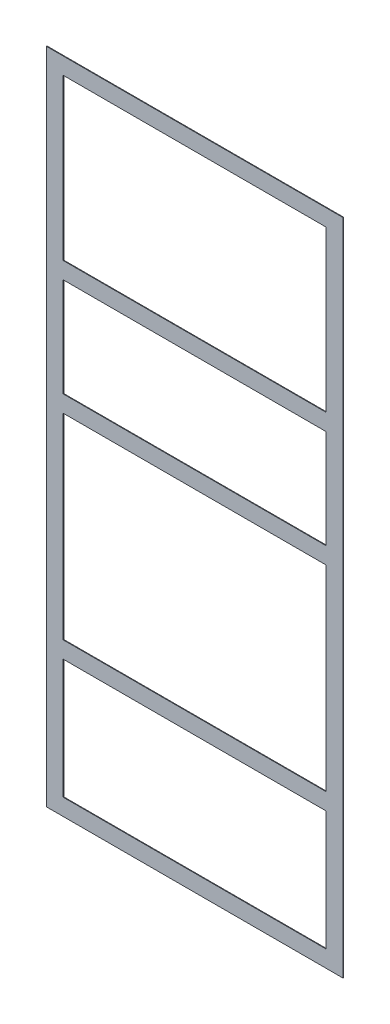
SolidWorks part; units mm, degrees
ref_plane "Alzado" through (0, 0, 0) normal (0, 0, 1) x (1, 0, 0)
ref_plane "Planta" through (0, 0, 0) normal (0, 1, 0) x (1, 0, 0)
ref_plane "Vista lateral" through (0, 0, 0) normal (1, 0, 0) x (0, 0, -1)
sketch "Croquis1" plane through (0, 0, 0) normal (0, 0, 1) x (1, 0, 0)
  line L1 (-450, 1000) -> (450, 1000)
  line L2 (-450, 1000) -> (-450, -1000)
  line L3 (-450, -1000) -> (450, -1000)
  line L4 (450, 1000) -> (450, -1000)
  line L5 (-450, 1000) -> (450, -1000) construction
  line L6 (-450, -1000) -> (450, 1000) construction
  point P0 (0, 0)
  dimension "D1" = 2000
  dimension "D2" = 900
extrude "Saliente-Extruir1" add sketch "Croquis1" along normal blind 1.9
sketch "Croquis2" plane through (0, 0, 1.9) normal (0, 0, 1) x (1, 0, 0)
  line L0 (-450, -1000) -> (450, -1000) construction
  line L1 (-399.2, 949.2) -> (399.2, 949.2)
  line L2 (-399.2, 949.2) -> (-399.2, -949.2)
  line L3 (-399.2, -949.2) -> (399.2, -949.2)
  line L4 (399.2, 949.2) -> (399.2, -949.2)
  line L5 (-399.2, 949.2) -> (399.2, -949.2) construction
  line L6 (-399.2, -949.2) -> (399.2, 949.2) construction
  line L7 (450, -1000) -> (450, 1000) construction
  line L8 (-399.2, 462.2) -> (399.2, 462.2)
  line L9 (-399.2, -586.2) -> (399.2, -586.2)
  line L10 (-399.2, -586.2) -> (-399.2, -949.2)
  line L11 (-399.2, -949.2) -> (399.2, -949.2)
  line L12 (399.2, -586.2) -> (399.2, -949.2)
  line L13 (-399.2, -586.2) -> (399.2, -949.2) construction
  line L14 (-399.2, -949.2) -> (399.2, -586.2) construction
  line L15 (-399.2, 60.6) -> (399.2, 60.6)
  line L16 (-399.2, 60.6) -> (-399.2, -535.4)
  line L17 (-399.2, -535.4) -> (399.2, -535.4)
  line L18 (399.2, 60.6) -> (399.2, -535.4)
  line L19 (-399.2, 60.6) -> (399.2, -535.4) construction
  line L20 (-399.2, -535.4) -> (399.2, 60.6) construction
  line L21 (-399.2, 411.4) -> (399.2, 411.4)
  line L22 (-399.2, 411.4) -> (-399.2, 111.4)
  line L23 (-399.2, 111.4) -> (399.2, 111.4)
  line L24 (399.2, 411.4) -> (399.2, 111.4)
  line L25 (-399.2, 411.4) -> (399.2, 111.4) construction
  line L26 (-399.2, 111.4) -> (399.2, 411.4) construction
  point P0 (0, 0)
  point P10 (0, -767.7)
  point P11 (0, -237.4)
  point P18 (0, 261.4)
  dimension "D1" = 50.8
  dimension "D2" = 50.8
  dimension "D3" = 363
  dimension "D4" = 50.8
  dimension "D5" = 596
  dimension "D6" = 50.8
  dimension "D7" = 300
  dimension "D8" = 50.8
extrude "Cortar-Extruir1" cut sketch "Croquis2" against normal blind 1.9 contours L9 L2 L3 L4 | L2 L17 L4 L15 | L2 L23 L4 L21 | L2 L8 L4 L1
